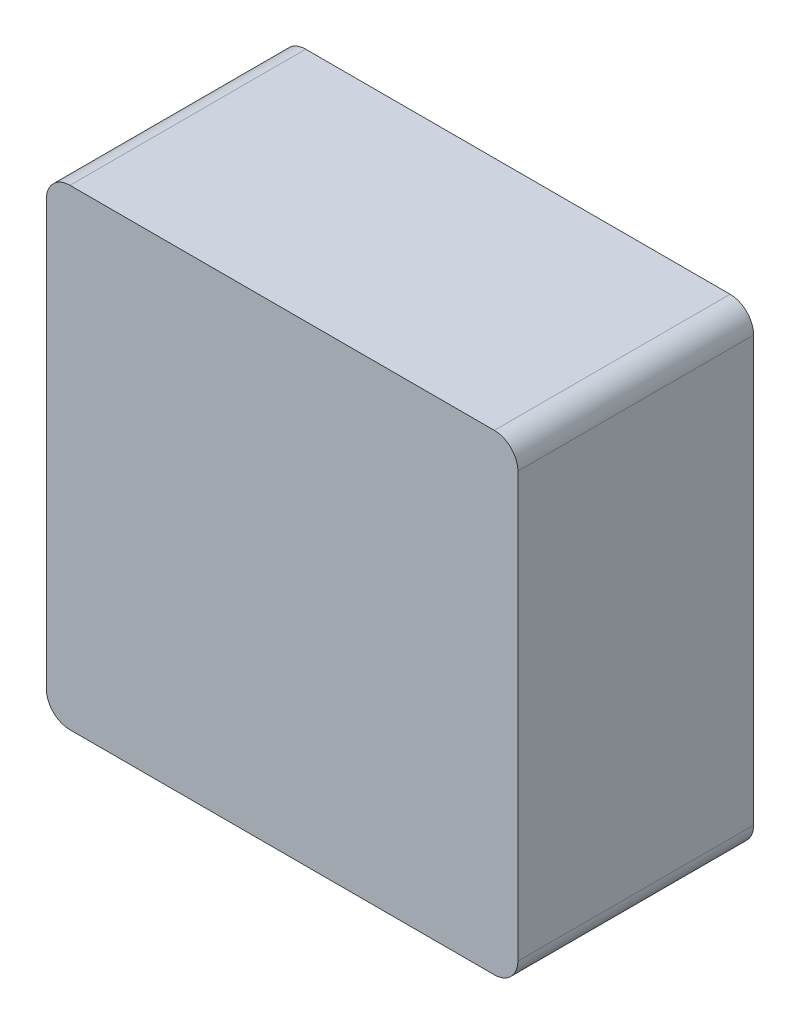
SolidWorks part; units mm, degrees
ref_plane "前视基准面" through (0, 0, 0) normal (0, 0, 1) x (1, 0, 0)
ref_plane "上视基准面" through (0, 0, 0) normal (0, 1, 0) x (1, 0, 0)
ref_plane "右视基准面" through (0, 0, 0) normal (1, 0, 0) x (0, 0, -1)
sketch "草图1" plane through (0, 0, 0) normal (0, 0, 1) x (1, 0, 0)
  circle A0 centre (0, 0) radius 50
  dimension "D1" = 100
extrude "凸台-拉伸1" add sketch "草图1" along normal blind 50
sketch "草图2" plane through (0, 0, 50) normal (0, 0, 1) x (1, 0, 0)
  line L1 (-100, 100) -> (100, 100)
  line L2 (-100, 100) -> (-100, -100)
  line L3 (-100, -100) -> (100, -100)
  line L4 (100, 100) -> (100, -100)
  dimension "D1" = 100
  dimension "D2" = 100
  dimension "D3" = 100
  dimension "D4" = 100
extrude "凸台-拉伸2" add sketch "草图2" along normal blind 100
fillet "圆角1" radius 10 6 edges at (50, 0, 0) (50, 0, 50) (100, 100, 100) (100, -100, 100) (-100, -100, 100) (-100, 100, 100)
